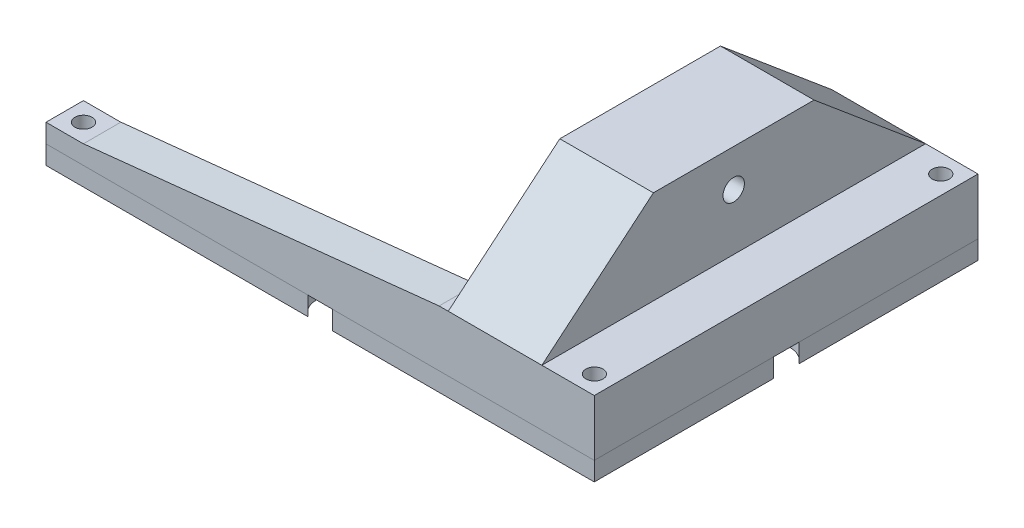
SolidWorks part; units mm, degrees
ref_plane "Спереди" through (0, 0, 0) normal (0, 0, 1) x (1, 0, 0)
ref_plane "Сверху" through (0, 0, 0) normal (0, 1, 0) x (1, 0, 0)
ref_plane "Справа" through (0, 0, 0) normal (1, 0, 0) x (0, 0, -1)
ref_plane "Плоскость4" through (0, 246.196, 0) normal (0, 1, 0) x (1, 0, 0)
sketch "Эскиз1" plane through (0, 246.196, 0) normal (0, 1, 0) x (1, 0, 0)
  line L1 (138.0105, -19.1124) -> (138.0105, 19.1124) construction
  line L2 (24.1587, -38.2731) -> (-24.1587, -38.2731) construction
  line L4 (-8.441, -140.7731) -> (138.0105, -140.7731) construction
  line L6 (138.0105, -140.7731) -> (138.0105, -38.2731)
  line L8 (-8.25, -130.7731) -> (8.25, -130.7731) construction
  line L11 (99.0105, -130.7731) -> (99.0105, -48.2731)
  line L12 (128.059, -48.2731) -> (1.559, -48.2731) construction
  line L16 (99.0105, -130.7731) -> (-8.441, -130.7731)
  line L17 (-8.441, 5.5) -> (-8.441, -5.5) construction
  line L18 (-8.441, -130.7731) -> (-8.441, -140.7731)
  line L19 (-8.441, -140.7731) -> (138.0105, -140.7731)
  line L21 (-8.441, -48.2731) -> (-8.441, -38.2731)
  line L23 (138.0105, -38.2731) -> (99.0105, -38.2731)
  line L24 (99.0105, -38.2731) -> (99.0105, -48.2731)
  circle A0 centre (133.059, -43.2731) radius 2.3
  circle A1 centre (133.059, -89.5231) radius 6
  circle A2 centre (133.059, -135.7731) radius 2.3
  circle A4 centre (64.809, -135.7731) radius 6
  circle A6 centre (-3.441, -135.7731) radius 2.3
extrude "Бобышка-Вытянуть1" add sketch "Эскиз1" along normal blind 5
ref_plane "Плоскость5" through (0, 251.196, 0) normal (0, 1, 0) x (1, 0, 0)
sketch "Эскиз2" plane through (0, 251.196, 0) normal (0, 1, 0) x (1, 0, 0)
  line L2 (138.0105, -38.2731) -> (138.0105, -140.7731)
  line L3 (68.1256, -140.7731) -> (138.0105, -140.7731) construction
  line L4 (138.0105, -19.1124) -> (138.0105, 19.1124) construction
  line L5 (138.0105, -140.7731) -> (-8.441, -140.7731)
  line L6 (-8.441, 5.5) -> (-8.441, -5.5) construction
  line L7 (-8.441, -140.7731) -> (-8.441, -130.7731)
  line L8 (-8.441, -130.7731) -> (99.0105, -130.7731)
  line L13 (99.0105, -130.7731) -> (99.0105, -38.2731)
  line L14 (99.0105, -38.2731) -> (138.0105, -38.2731)
  circle A1 centre (-3.441, -135.7731) radius 2.3
  circle A2 centre (133.059, -135.7731) radius 2.3
  circle A3 centre (133.059, -43.2731) radius 2.3
  point P1 (0, 0)
extrude "Бобышка-Вытянуть2" add sketch "Эскиз2" along normal blind 15 separate body contours L14 L13 L8 L7 L5 L2 A3 A2 A1
ref_plane "Плоскость6" through (0, 266.196, 0) normal (0, 1, 0) x (1, 0, 0)
sketch "Эскиз3" plane through (0, 266.196, 0) normal (0, 1, 0) x (1, 0, 0)
  line L0 (99.0105, -38.2731) -> (99.0105, -140.7731)
  line L3 (99.0105, -140.7731) -> (124.0105, -140.7731)
  line L4 (124.0105, -140.7731) -> (124.0105, -38.2731)
  line L5 (124.0105, -38.2731) -> (99.0105, -38.2731)
  point P4 (0, 0)
  point P9 (0, 0)
  point P10 (0, 0)
  point P11 (0, 0)
extrude "Бобышка-Вытянуть3" add sketch "Эскиз3" along normal blind 25
ref_plane "Плоскость7" through (124.0105, 0, 0) normal (1, 0, 0) x (0, 0, -1)
sketch "Эскиз4" plane through (124.0105, 0, 0) normal (1, 0, 0) x (0, 0, -1)
  circle A0 centre (-89.5231, 281.196) radius 2.86
extrude "Вырез-Вытянуть1" cut sketch "Эскиз4" against normal through all both and the other way through all
chamfer "Фаска1" distance 25 angle 50 2 edges at (111.5105, 291.196, 140.7731) (111.5105, 291.196, 38.2731)
ref_plane "Плоскость8" through (0, 266.196, 0) normal (0, 1, 0) x (1, 0, 0)
sketch "Эскиз5" plane through (0, 266.196, 0) normal (0, 1, 0) x (1, 0, 0)
  line L4 (-8.441, 5.5) -> (-8.441, -5.5) construction
  line L7 (-8.441, -130.7731) -> (-8.441, -140.7731)
  line L9 (-8.441, -140.7731) -> (1.559, -140.7731)
  line L11 (1.559, -140.7731) -> (1.559, -130.7731)
  line L13 (1.559, -130.7731) -> (-8.441, -130.7731)
  point P0 (0, 0)
extrude "Вырез-Вытянуть2" cut sketch "Эскиз5" against normal blind 10
chamfer "Фаска2" distance 95 angle 6 1 edges at (1.559, 266.196, 135.7731)
